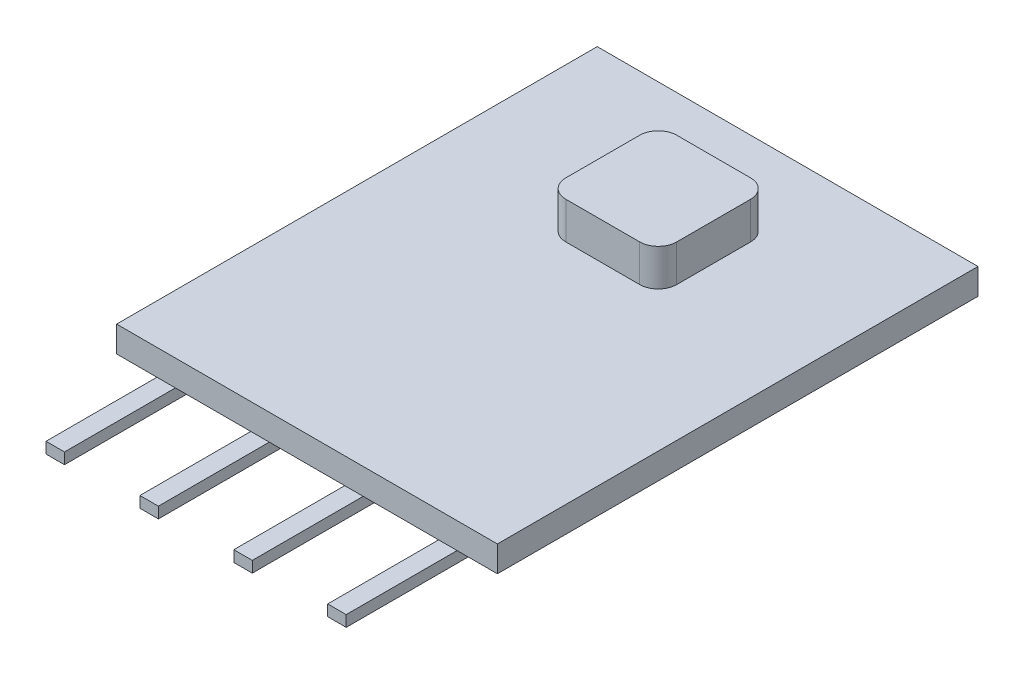
SolidWorks part; units mm, degrees
ref_plane "Front" through (0, 0, 0) normal (0, 0, 1) x (1, 0, 0)
ref_plane "Top" through (0, 0, 0) normal (0, 1, 0) x (1, 0, 0)
ref_plane "Right" through (0, 0, 0) normal (1, 0, 0) x (0, 0, -1)
sketch "Эскиз1" plane through (0, 0, 0) normal (0, 1, 0) x (1, 0, 0)
  line L1 (-5.15, -6.5) -> (5.15, -6.5)
  line L2 (-5.15, -6.5) -> (-5.15, 6.5)
  line L3 (-5.15, 6.5) -> (5.15, 6.5)
  line L4 (5.15, -6.5) -> (5.15, 6.5)
  line L5 (-5.15, -6.5) -> (5.15, 6.5) construction
  line L6 (-5.15, 6.5) -> (5.15, -6.5) construction
  point P0 (0, 0)
  dimension "D1" = 10.3
  dimension "D2" = 13
extrude "Бобышка-Вытянуть1" add sketch "Эскиз1" along normal blind 0.7
sketch "Эскиз2" plane through (0, 0.7, 0) normal (0, 1, 0) x (1, 0, 0)
  line L0 (5.15, 6.5) -> (-5.15, 6.5) construction
  line L1 (-1.5, 4.5) -> (1.5, 4.5)
  line L2 (-1.5, 4.5) -> (-1.5, 1.5)
  line L3 (-1.5, 1.5) -> (1.5, 1.5)
  line L4 (1.5, 4.5) -> (1.5, 1.5)
  line L5 (-1.5, 4.5) -> (1.5, 1.5) construction
  line L6 (-1.5, 1.5) -> (1.5, 4.5) construction
  point P0 (0, 3)
  dimension "D1" = 2
  dimension "D2" = 3
extrude "Бобышка-Вытянуть2" add sketch "Эскиз2" along normal blind 1 separate body
fillet "Скругление1" radius 0.5 4 edges at (-1.5, 1.2, -4.5) (1.5, 1.2, -4.5) (-1.5, 1.2, -1.5) (1.5, 1.2, -1.5)
sketch "Эскиз3" plane through (0, 0, 0) normal (0, -1, 0) x (1, 0, 0)
  line L0 (-5.15, 6.5) -> (5.15, 6.5) construction
  line L1 (-3.56, 6) -> (-4.06, 6)
  line L2 (-3.56, 6) -> (-3.56, 6.5)
  line L3 (-3.56, 6.5) -> (-4.06, 6.5)
  line L4 (-4.06, 6) -> (-4.06, 6.5)
  line L5 (-3.56, 6) -> (-4.06, 6.5) construction
  line L6 (-3.56, 6.5) -> (-4.06, 6) construction
  point P0 (-3.81, 6.25)
  dimension "D1" = 0.5
  dimension "D2" = 3.81
extrude "Бобышка-Вытянуть3" add sketch "Эскиз3" along normal blind 0.3 separate body
sketch "Эскиз4" plane through (0, 0, 6.5) normal (0, 0, 1) x (1, 0, 0)
  line L1 (-3.56, -0.3) -> (-4.06, -0.3)
  line L2 (-3.56, -0.3) -> (-3.56, 0)
  line L3 (-3.56, 0) -> (-4.06, 0)
  line L4 (-4.06, -0.3) -> (-4.06, 0)
extrude "Бобышка-Вытянуть4" add sketch "Эскиз4" along normal blind 3
pattern_linear "Линейный массив1" count 4 spacing 2.54 along (1, 0, 0) of "Бобышка-Вытянуть3", "Бобышка-Вытянуть4"
